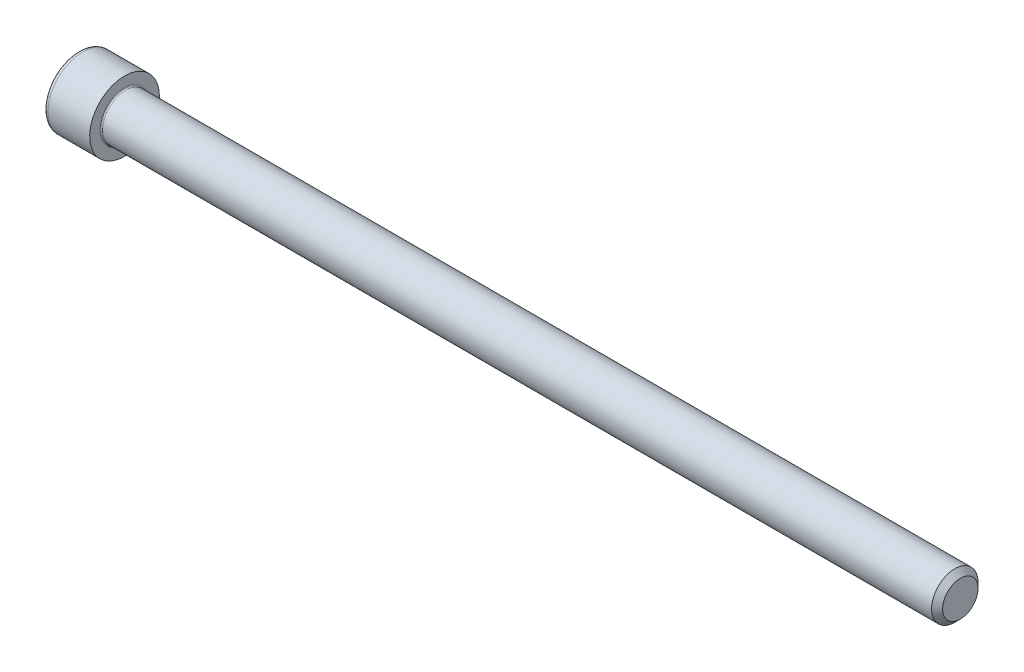
SolidWorks part; units mm, degrees
ref_plane "Front Plane" through (0, 0, 0) normal (0, 0, 1) x (1, 0, 0)
ref_plane "Top Plane" through (0, 0, 0) normal (0, 1, 0) x (1, 0, 0)
ref_plane "Right Plane" through (0, 0, 0) normal (1, 0, 0) x (0, 0, -1)
ref_plane "Plane1"
sketch "Sketch1" plane through (0, 0, 0) normal (0, 0, 1) x (1, 0, 0)
  line L0 (-1.7103, 0) -> (114.3, 0)
  line L1 (114.3, 0) -> (114.3, 3.175)
  line L2 (114.3, 3.175) -> (88.9, 3.175)
  line L3 (88.9, 3.175) -> (85.7249, 3.175)
  line L4 (85.7249, 3.175) -> (0, 3.175)
  line L5 (0, 3.175) -> (0, 4.7625)
  line L6 (0, 4.7625) -> (-6.35, 4.7625)
  line L7 (-6.35, 4.7625) -> (-6.35, 2.757)
  line L8 (-6.35, 2.757) -> (-3.302, 2.757)
  line L9 (-3.302, 2.757) -> (-1.7103, 0)
  line L10 (-1.7103, 0) -> (114.3, 0) construction
  dimension "D1" = 270
  dimension "D2" = 3.1751
  dimension "D3" = 6.35
  dimension "D4" = 3.048
  dimension "D5" = 120
  dimension "D6" = 3.175
  dimension "D7" = 3.175
  dimension "D8" = 2.757
  dimension "D9" = 4.7625
  dimension "D10" = 90
revolve "Body" add sketch "Sketch1" angle 360 about L10
cosmetic thread "Cosmetic Thread1" parameters "D1"=25.4, "D2"=4.8387
ref_plane "Plane2"
sketch "Sketch2" plane through (-6.35, 0, 0) normal (-1, 0, 0) x (0, 0, 1)
  line L0 (2.757, 0) -> (1.3785, -2.3876)
  line L1 (1.3785, -2.3876) -> (-1.3785, -2.3876)
  line L2 (-1.3785, -2.3876) -> (-2.757, 0)
  line L3 (-2.757, 0) -> (-1.3785, 2.3876)
  line L4 (-1.3785, 2.3876) -> (1.3785, 2.3876)
  line L5 (1.3785, 2.3876) -> (2.757, 0)
  circle A0 centre (0, 0) radius 2.757
extrude "Slot" add sketch "Sketch2" against normal up to next contours L0 A0 | L1 A0 | L2 A0 | L3 A0 | L4 A0 | L5 A0
fillet "Thread" radius 0.635 1 edges at (-6.35, -4.7625, 0)
chamfer "Chamfer1" distance 0.7556 distance2 0.7556 1 edges at (114.3, -3.175, 0)
fillet "Fillet2" radius 0.1778 1 edges at (0, -3.175, 0)
